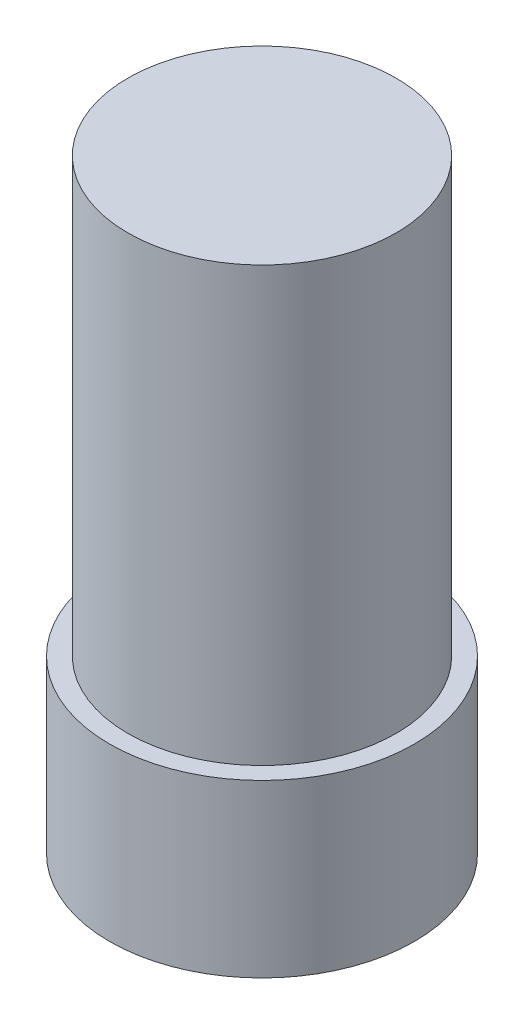
SolidWorks part; units mm, degrees
ref_plane "Front Plane" through (0, 0, 0) normal (0, 0, 1) x (1, 0, 0)
ref_plane "Top Plane" through (0, 0, 0) normal (0, 1, 0) x (1, 0, 0)
ref_plane "Right Plane" through (0, 0, 0) normal (1, 0, 0) x (0, 0, -1)
sketch "Sketch2" plane through (0, 0, 0) normal (0, 1, 0) x (1, 0, 0)
  circle A0 centre (0, 0) radius 19.6
  circle A1 centre (0, 0) radius 12.25
  dimension "D1" = 24.5
  dimension "D2" = 39.2
extrude "Boss-Extrude1" add sketch "Sketch2" along normal blind 22
sketch "Sketch3" plane through (0, 22, 0) normal (0, 1, 0) x (1, 0, 0)
  circle A0 centre (0, 0) radius 17.25
  dimension "D1" = 34.5
extrude "Boss-Extrude2" add sketch "Sketch3" along normal blind 55.75 and the other way blind 13
